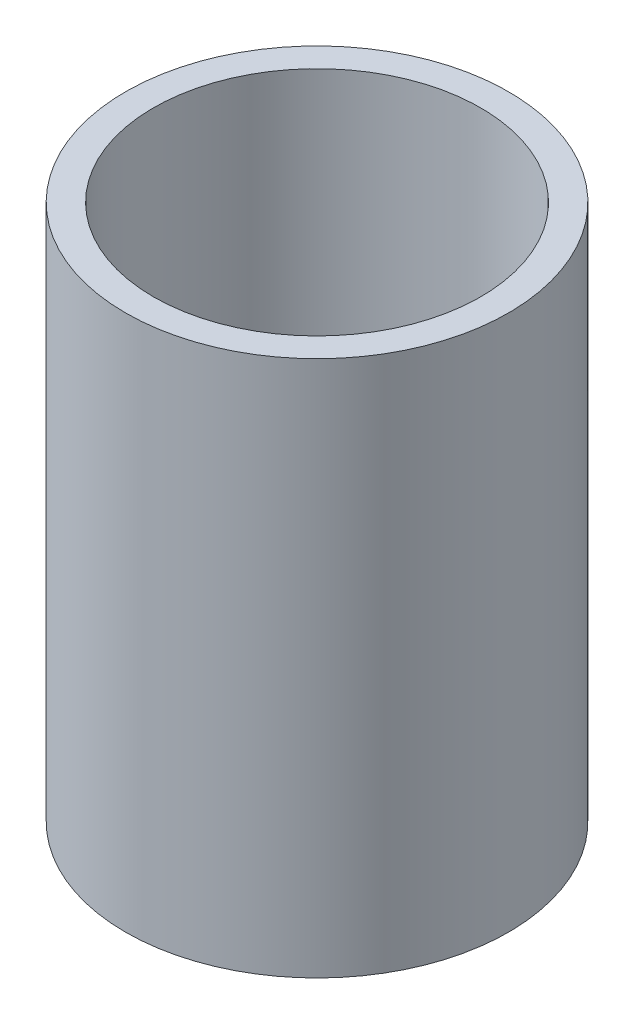
SolidWorks part; units mm, degrees
ref_plane "Alzado" through (0, 0, 0) normal (0, 0, 1) x (1, 0, 0)
ref_plane "Planta" through (0, 0, 0) normal (0, 1, 0) x (1, 0, 0)
ref_plane "Vista lateral" through (0, 0, 0) normal (1, 0, 0) x (0, 0, -1)
sketch "Croquis1" plane through (0, 0, 0) normal (0, 1, 0) x (1, 0, 0)
  circle A0 centre (0, 0) radius 27.5
  circle A1 centre (0, 0) radius 23.5
  dimension "D1" = 55
  dimension "D2" = 47
extrude "Saliente-Extruir1" add sketch "Croquis1" along normal blind 77
